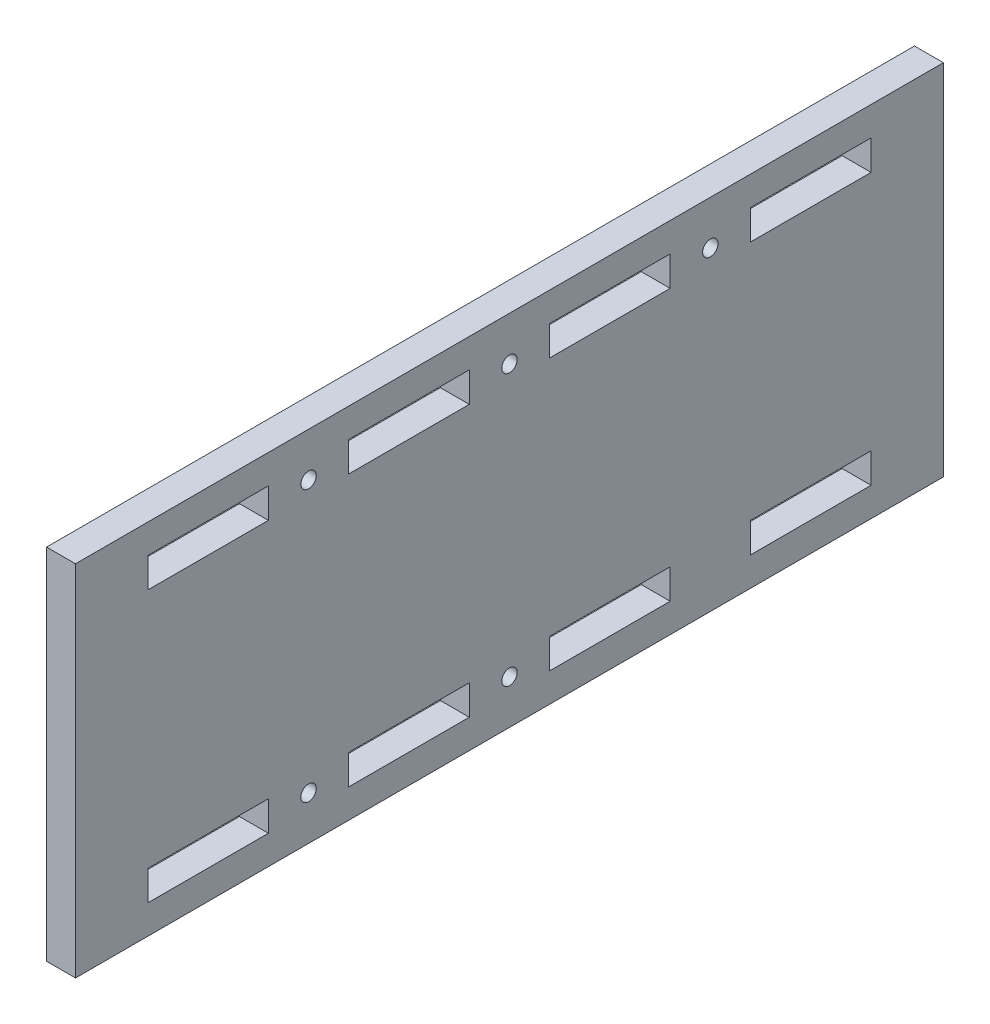
SolidWorks part; units mm, degrees
material "Oak"
ref_plane "Front Plane" through (0, 0, 0) normal (0, 0, 1) x (1, 0, 0)
ref_plane "Top Plane" through (0, 0, 0) normal (0, 1, 0) x (1, 0, 0)
ref_plane "Right Plane" through (0, 0, 0) normal (1, 0, 0) x (0, 0, -1)
sketch "Sketch1" plane through (0, 0, 0) normal (1, 0, 0) x (0, 0, -1)
  line L0 (-33.3333, -25) -> (-33.3333, -31.2)
  line L1 (-90, -37.2) -> (90, -37.2)
  line L2 (-90, -37.2) -> (-90, 37.2)
  line L3 (-90, 37.2) -> (90, 37.2)
  line L4 (90, -37.2) -> (90, 37.2)
  line L5 (-90, -37.2) -> (90, 37.2) construction
  line L6 (-90, 37.2) -> (90, -37.2) construction
  line L7 (-75, -25) -> (-50, -25)
  line L8 (-75, -25) -> (-75, -31.2)
  line L9 (-75, -31.2) -> (-50, -31.2)
  line L10 (-50, -25) -> (-50, -31.2)
  line L11 (-33.3333, -25) -> (-8.3333, -25)
  line L12 (-8.3333, -25) -> (-8.3333, -31.2)
  line L13 (-33.3333, -31.2) -> (-8.3333, -31.2)
  line L14 (8.3333, -25) -> (8.3333, -31.2)
  line L15 (8.3333, -25) -> (33.3333, -25)
  line L16 (33.3333, -25) -> (33.3333, -31.2)
  line L17 (8.3333, -31.2) -> (33.3333, -31.2)
  line L18 (50, -25) -> (50, -31.2)
  line L19 (50, -25) -> (75, -25)
  line L20 (75, -25) -> (75, -31.2)
  line L21 (50, -31.2) -> (75, -31.2)
  line L22 (-50, -28.1) -> (-33.3333, -28.1) construction
  line L23 (-8.3333, -28.1) -> (8.3333, -28.1) construction
  line L24 (-75, 31.2) -> (-75, 25)
  line L25 (-75, 31.2) -> (-50, 31.2)
  line L26 (-50, 31.2) -> (-50, 25)
  line L27 (-75, 25) -> (-50, 25)
  line L28 (-33.3333, 31.2) -> (-33.3333, 25)
  line L29 (-33.3333, 25) -> (-8.3333, 25)
  line L30 (-8.3333, 31.2) -> (-8.3333, 25)
  line L31 (-33.3333, 31.2) -> (-8.3333, 31.2)
  line L32 (8.3333, 31.2) -> (8.3333, 25)
  line L33 (8.3333, 25) -> (33.3333, 25)
  line L34 (33.3333, 31.2) -> (33.3333, 25)
  line L35 (8.3333, 31.2) -> (33.3333, 31.2)
  line L36 (50, 31.2) -> (50, 25)
  line L37 (50, 25) -> (75, 25)
  line L38 (75, 31.2) -> (75, 25)
  line L39 (50, 31.2) -> (75, 31.2)
  line L40 (0, 3.3) -> (0, -3.3) construction
  circle A0 centre (-41.6667, -28.1) radius 1.6
  circle A1 centre (0, -28.1) radius 1.6
  circle A3 centre (41.6667, -28.1) radius 1.6 [skipped]
  circle A4 centre (-41.6667, 28.1) radius 1.6
  circle A5 centre (0, 28.1) radius 1.6
  circle A6 centre (41.6667, 28.1) radius 1.6
  point P0 (0, 0)
  dimension "D9" = 3.2
  dimension "D1" = 180
  dimension "D2" = 15
  dimension "D3" = 25
  dimension "D4" = 6
  dimension "D5" = 6.2
  dimension "D6" = 6
  dimension "D7" = 4
  dimension "D8" = 15
  dimension "D12" = 50
  dimension "D10" = 3
  dimension "D11" = 2
extrude "Boss-Extrude1" add sketch "Sketch1" along normal blind 6
